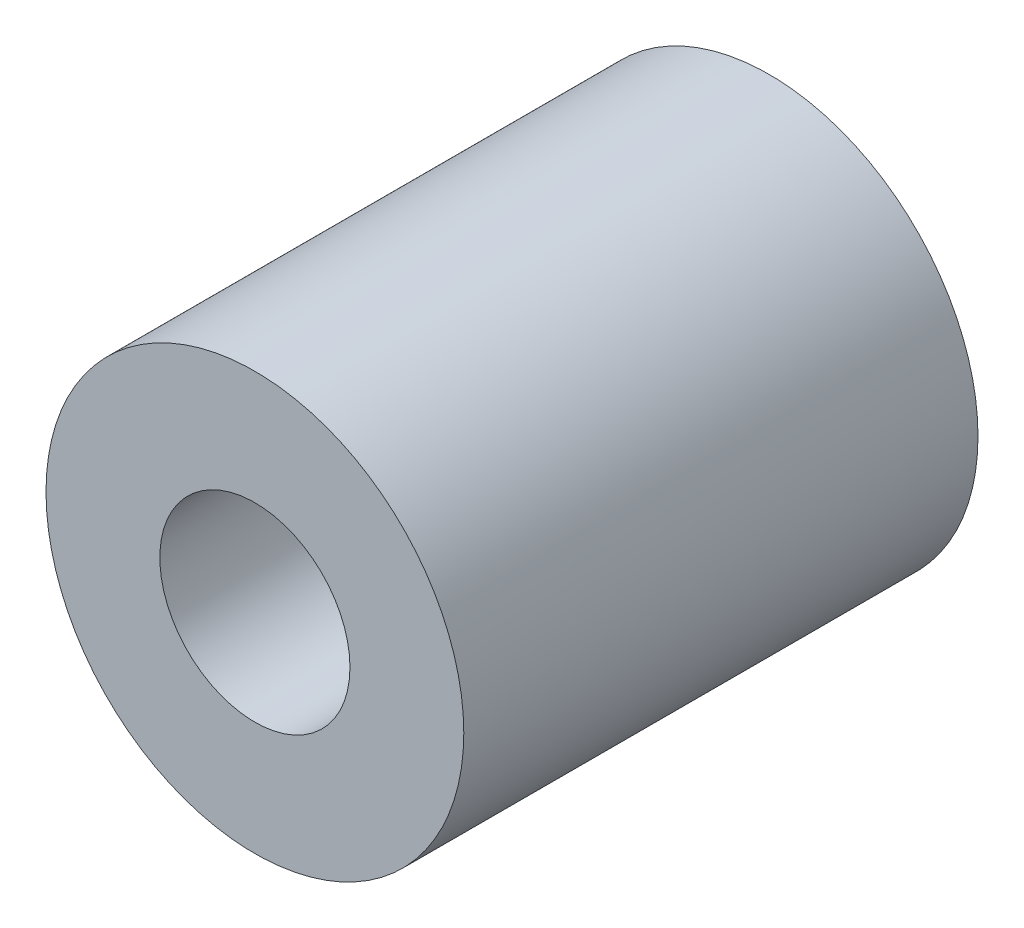
SolidWorks part; units mm, degrees
ref_plane "Ön Düzlem" through (0, 0, 0) normal (0, 0, 1) x (1, 0, 0)
ref_plane "Üst Düzlem" through (0, 0, 0) normal (0, 1, 0) x (1, 0, 0)
ref_plane "Sağ Düzlem" through (0, 0, 0) normal (1, 0, 0) x (0, 0, -1)
sketch "Çizim1" plane through (0, 0, 0) normal (0, 0, 1) x (1, 0, 0)
  circle A0 centre (0, 0) radius 3.9
  circle A1 centre (0, 0) radius 1.775
  dimension "D1" = 7.8
  dimension "D2" = 3.55
extrude "Yükseklik-Ekstrüzyon1" add sketch "Çizim1" along normal blind 9.6
